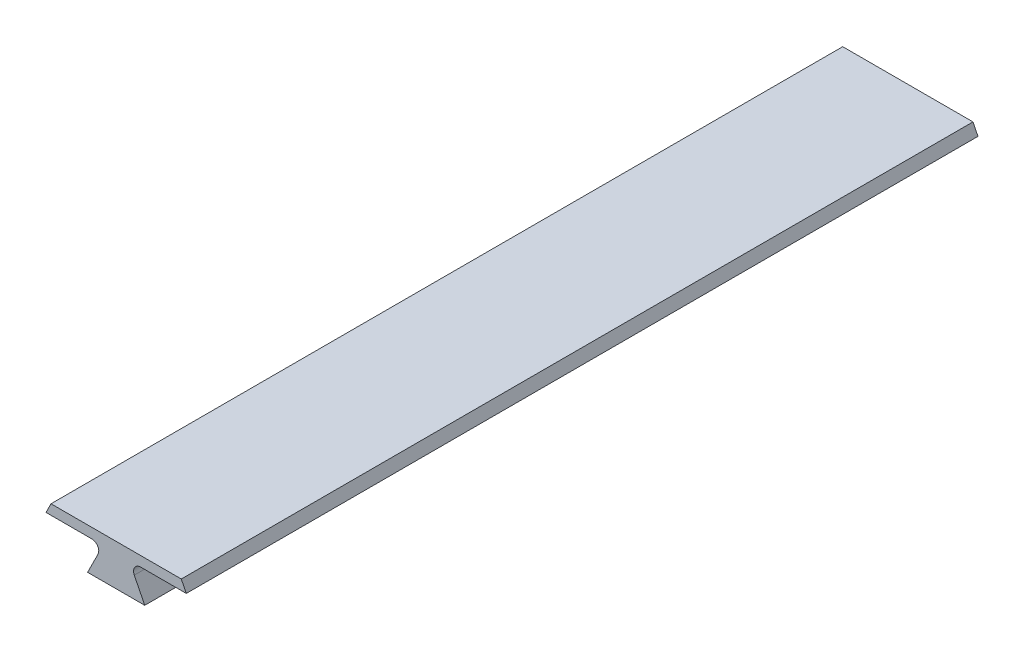
SolidWorks part; units mm, degrees
ref_plane "Front Plane" through (0, 0, 0) normal (0, 0, 1) x (1, 0, 0)
ref_plane "Top Plane" through (0, 0, 0) normal (0, 1, 0) x (1, 0, 0)
ref_plane "Right Plane" through (0, 0, 0) normal (1, 0, 0) x (0, 0, -1)
sketch "Sketch1" plane through (0, 0, 0) normal (0, 0, -1) x (1, 0, 0)
  line L0 (-3.5, 46) -> (-1.2177, 46)
  line L1 (-0.875, 46) -> (-1.75, 47.75) construction
  line L2 (-1.75, 47.75) -> (1.75, 47.75) construction
  line L3 (1.75, 47.75) -> (0.875, 46) construction
  line L4 (1.2177, 46) -> (3.5, 46)
  line L5 (-0.875, 46) -> (0.875, 46) construction
  line L6 (0, 46) -> (0, 47.75) construction
  line L7 (-3.5, 46) -> (-3.5, 44.6758) construction
  line L8 (-3.25, 45.5) -> (3.25, 45.5)
  line L9 (0, 0) -> (0, 45.5) construction
  line L10 (0, 46) -> (0, 45.5) construction
  line L11 (-0.9047, 46.5065) -> (-1.4264, 47.55)
  line L12 (-1.4264, 47.55) -> (1.4264, 47.55)
  line L13 (1.4264, 47.55) -> (0.9047, 46.5065)
  line L14 (1.4264, 47.55) -> (0.6961, 46.0894) construction
  line L15 (-0.6961, 46.0894) -> (-1.4264, 47.55) construction
  line L16 (1.2368, 46.7236) -> (0, 46.7236) construction
  line L17 (0, 46.7236) -> (-1.2368, 46.7236) construction
  line L18 (0, 0) -> (87.3462, 0) construction
  line L19 (-3.5, 46) -> (-3.25, 45.5)
  line L20 (3.25, 45.5) -> (3.5, 46)
  arc A0 (1.2177, 46) -> (0.9047, 46.5065) centre (1.2177, 46.35) cw
  arc A1 (-1.2177, 46) -> (-0.9047, 46.5065) centre (-1.2177, 46.35) ccw
  arc A4 (1.2368, 46.7236) -> (1.684, 46) centre (1.684, 46.5) ccw construction
  point P10 (0, 0)
  dimension "D6" = 7
  dimension "D9" = 0.5
  dimension "D10" = 0.35
  dimension "D1" = 1.75
  dimension "D2" = 3.5
  dimension "D3" = 1.75
  dimension "D4" = 46
  dimension "D5" = 0.2
  dimension "D7" = 6.5
  dimension "D8" = 0.5
  dimension "D11" = 26.565
extrude "Boss-Extrude1" add sketch "Sketch1" along normal blind 34.5 contours L8 L20 L4 A0 L13 L12 L11 A1 L0 L19
sketch "Sketch2" plane through (0, 0, 0) normal (1, 0, 0) x (0, 0, -1)
  line L0 (34.5, -46) -> (0, -46) construction
  line L1 (1.7, -46) -> (8.2, -46)
  line L2 (1.7, -46) -> (1.7, -47.55)
  line L3 (1.7, -47.55) -> (8.2, -47.55)
  line L4 (8.2, -46) -> (8.2, -47.55)
  line L5 (4.95, -47.55) -> (4.95, -46) construction
  line L6 (1.7, -46.775) -> (8.2, -46.775) construction
  line L7 (34.5, -47.55) -> (0, -47.55) construction
  line L8 (34.5, -46) -> (0, -46) construction
  line L9 (26.3, -47.55) -> (32.8, -47.55)
  line L10 (26.3, -47.55) -> (26.3, -46)
  line L11 (26.3, -46) -> (32.8, -46)
  line L12 (32.8, -47.55) -> (32.8, -46)
  line L13 (29.55, -46) -> (29.55, -47.55) construction
  line L14 (26.3, -46.775) -> (32.8, -46.775) construction
  line L15 (16.4, -46.775) -> (18.1, -46.775) construction
  line L16 (18.1, -47.55) -> (24.6, -47.55)
  line L17 (8.2, -46.775) -> (9.9, -46.775) construction
  line L18 (9.9, -46) -> (16.4, -46)
  line L19 (9.9, -46) -> (9.9, -47.55)
  line L20 (9.9, -47.55) -> (16.4, -47.55)
  line L21 (16.4, -46) -> (16.4, -47.55)
  line L22 (13.15, -47.55) -> (13.15, -46) construction
  line L23 (9.9, -46.775) -> (16.4, -46.775) construction
  line L24 (18.1, -47.55) -> (18.1, -46)
  line L25 (1.7, -46.775) -> (0, -46.775) construction
  line L26 (0, -47.55) -> (0, -46.5065) construction
  line L27 (32.8, -46.775) -> (34.5, -46.775) construction
  line L28 (34.5, -47.55) -> (34.5, -46.5065) construction
  line L29 (18.1, -46) -> (24.6, -46)
  line L30 (24.6, -47.55) -> (24.6, -46)
  line L31 (21.35, -46) -> (21.35, -47.55) construction
  line L32 (18.1, -46.775) -> (24.6, -46.775) construction
  line L33 (24.6, -46.775) -> (26.3, -46.775) construction
  point P14 (23.7893, -47.55)
  point P96 (29.55, -46.775)
  point P120 (13.15, -46.775)
  point P140 (4.95, -46.775)
  point P148 (21.35, -46.775)
  dimension "D1" = 1.7
extrude "Cut-Extrude1" cut sketch "Sketch2" against normal through all both and the other way through all
sketch "Sketch3" plane through (0, 0, -34.5) normal (0, 0, -1) x (-1, 0, 0)
  line L0 (1.2177, -46) -> (-1.2177, -46)
  line L8 (3.5, -46) -> (3.25, -45.5)
  line L9 (3.25, -45.5) -> (-3.25, -45.5)
  line L10 (-3.25, -45.5) -> (-3.5, -46)
  line L11 (-3.5, -46) -> (-1.2177, -46)
  line L12 (-0.9047, -46.5065) -> (-1.4264, -47.55)
  line L13 (-1.4264, -47.55) -> (1.4264, -47.55)
  line L14 (1.4264, -47.55) -> (0.9047, -46.5065)
  line L15 (1.2177, -46) -> (3.5, -46)
  line L16 (3.5, -46) -> (3.25, -45.5)
  line L17 (3.25, -45.5) -> (-3.25, -45.5)
  line L18 (-3.25, -45.5) -> (-3.5, -46)
  line L19 (-3.5, -46) -> (-1.2177, -46)
  line L23 (1.2177, -46) -> (3.5, -46)
  arc A2 (-0.9047, -46.5065) -> (-1.2177, -46) centre (-1.2177, -46.35) ccw
  arc A3 (1.2177, -46) -> (0.9047, -46.5065) centre (1.2177, -46.35) ccw
  dimension "D1" = 0
extrude "Boss-Extrude2" add sketch "Sketch3" along normal blind 5
fillet "Fillet1" radius 0.2 6 edges at (0, -46, -32.8) (0, -46, -16.4) (0, -46, -26.3) (0, -46, -9.9) (0, -46, -8.2) (0, -46, -1.7)
